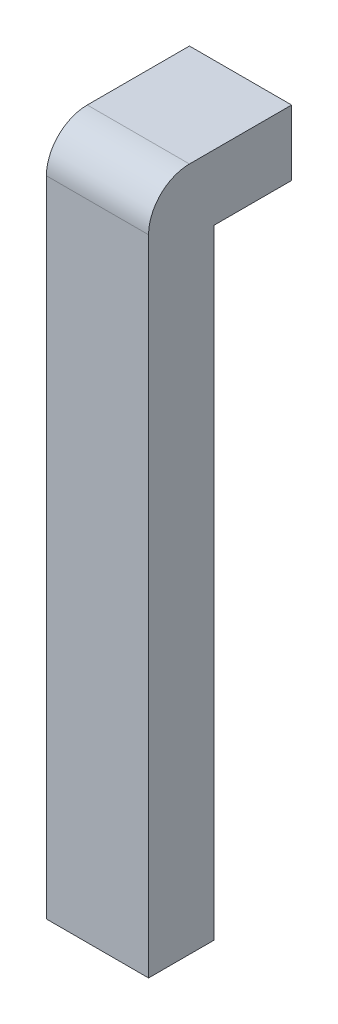
SolidWorks part; units mm, degrees
ref_plane "前视基准面" through (0, 0, 0) normal (0, 0, 1) x (1, 0, 0)
ref_plane "上视基准面" through (0, 0, 0) normal (0, 1, 0) x (1, 0, 0)
ref_plane "右视基准面" through (0, 0, 0) normal (1, 0, 0) x (0, 0, -1)
sketch "草图1" plane through (0, 0, 0) normal (0, 0, 1) x (1, 0, 0)
  line L1 (0, 0) -> (50, 0)
  line L2 (0, 0) -> (0, 55)
  line L3 (0, 55) -> (50, 55)
  line L4 (50, 0) -> (50, 55)
  dimension "D1" = 50
  dimension "D2" = 55
extrude "凸台-拉伸1" add sketch "草图1" along normal blind 70
sketch "草图3" plane through (0, 0, 0) normal (0, 0, -1) x (-1, 0, 0)
  line L0 (-50, 0) -> (-50, 55) construction
  line L1 (-50, 25) -> (0, 25)
  line L2 (-50, 25) -> (-50, 0)
  line L3 (-50, 0) -> (0, 0)
  line L4 (0, 25) -> (0, 0)
  dimension "D1" = 25
extrude "切除-拉伸1" cut sketch "草图3" against normal blind 38
sketch "草图4" plane through (0, 25, 0) normal (0, -1, 0) x (1, 0, 0)
  line L0 (12.2, 38) -> (37.7, 38)
  line L1 (37.7, 38) -> (37.7, 2)
  line L2 (37.7, 2) -> (12.2, 2)
  line L3 (12.2, 2) -> (12.2, 38)
  line L4 (0, 38) -> (0, 0) construction
  line L6 (0, 0) -> (50, 0) construction
  dimension "D1" = 36
  dimension "D2" = 25.5
  dimension "D3" = 12.2
  dimension "D4" = 2
extrude "切除-拉伸2" cut sketch "草图4" against normal blind 22
sketch "草图9" plane through (0, 0, 38) normal (0, 0, -1) x (-1, 0, 0)
  circle A0 centre (-27.6426, 19.7287) radius 0.7999
  circle A1 centre (-7.1435, 19.7287) radius 0.7999
  circle A2 centre (-27.442, 44.1402) radius 1
  circle A3 centre (-7.4474, 44.1402) radius 1
  dimension "D1" = 1.5999
  dimension "D2" = 2
  dimension "D3" = 2
sketch "草图12" plane through (0, 47, 0) normal (0, -1, 0) x (1, 0, 0)
  line L0 (37.7, 2) -> (37.7, 38) construction
  line L1 (12.2, 38) -> (37.7, 38)
  line L2 (12.2, 38) -> (12.2, 37)
  line L3 (12.2, 37) -> (37.7, 37)
  line L4 (37.7, 38) -> (37.7, 37)
  dimension "D1" = 1
extrude "凸台-拉伸2" add sketch "草图12" along normal blind 19
sketch "草图13" plane through (0, 25, 0) normal (0, -1, 0) x (1, 0, 0)
  line L0 (12.2, 38) -> (0, 38)
  line L1 (0, 38) -> (0, 0)
  line L2 (0, 0) -> (50, 0)
  line L3 (50, 0) -> (50, 38)
  line L4 (50, 38) -> (37.7, 38)
  line L5 (37.7, 38) -> (37.7, 2)
  line L6 (37.7, 2) -> (37.7, 37) construction
  line L7 (37.7, 2) -> (37.7, 38) construction
  line L8 (37.7, 2) -> (12.2, 2)
  line L9 (12.2, 2) -> (12.2, 38)
extrude "凸台-拉伸3" add sketch "草图13" along normal blind 2
sketch "草图16" plane through (0, 0, 0) normal (0, -1, 0) x (1, 0, 0)
  line L1 (0, 70) -> (50, 70)
  line L2 (0, 70) -> (0, 38)
  line L3 (0, 38) -> (50, 38)
  line L4 (50, 70) -> (50, 38)
extrude "凸台-拉伸5" add sketch "草图16" along normal blind 280
fillet "圆角1" radius 20 1 edges at (25, 55, 70)
sketch "草图23" plane through (0, 0, 0) normal (0, 0, -1) x (-1, 0, 0)
  line L0 (0, 55) -> (0, 23) construction
  line L1 (-50, 23) -> (-50, 55) construction
  line L2 (-50, 55) -> (0, 55) construction
  circle A0 centre (-15.2, 44.1402) radius 1
  circle A1 centre (-34.8, 44.1402) radius 1
  dimension "D1" = 2
  dimension "D2" = 15.2
  dimension "D3" = 15.2
  dimension "D4" = 2
  dimension "D5" = 10.8598
  dimension "D6" = 10.8598
extrude "切除-拉伸3" cut sketch "草图23" against normal blind 10
